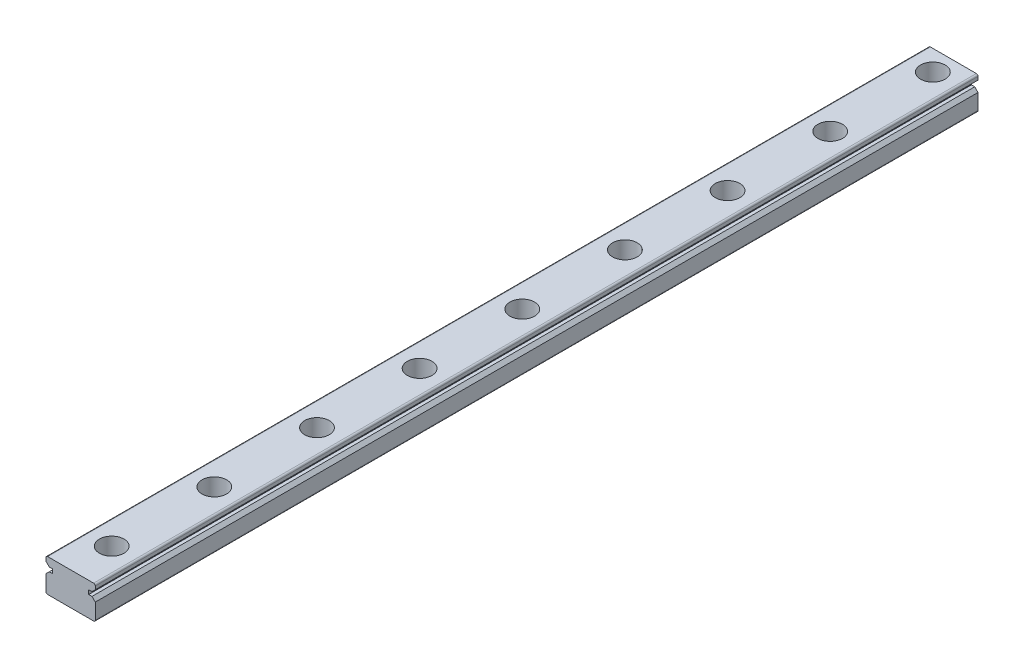
SolidWorks part; units mm, degrees
ref_plane "Front Plane" through (0, 0, 0) normal (0, 0, 1) x (1, 0, 0)
ref_plane "Top Plane" through (0, 0, 0) normal (0, 1, 0) x (1, 0, 0)
ref_plane "Right Plane" through (0, 0, 0) normal (1, 0, 0) x (0, 0, -1)
sketch "Sketch1" plane through (0, 0, 0) normal (0, 0, 1) x (1, 0, 0)
  line L0 (0, -1000) -> (0, 1.5) construction
  line L1 (-5.6, 4) -> (5.6, 4)
  line L2 (-6, 3.6) -> (-6, 2.8)
  line L3 (-5.6, -4) -> (5.6, -4)
  line L4 (6, 3.6) -> (6, 2.8)
  line L5 (-6, 4) -> (6, -4) construction
  line L6 (-6, -4) -> (6, 4) construction
  line L7 (6, 0.2) -> (6, -3.6)
  line L8 (-5.2, 2) -> (-4.4, 2)
  line L9 (-4.4, 2) -> (-4.4, 1)
  line L10 (-5.2, 1) -> (-4.4, 1)
  line L11 (4.4, 2) -> (4.4, 1)
  line L14 (-6, 0.2) -> (-6, -3.6)
  line L15 (4.4, 2) -> (5.2, 2)
  line L16 (4.4, 1) -> (5.2, 1)
  line L17 (0, 1.5) -> (0, 1001.8645) construction
  line L18 (-6, 2.8) -> (-5.2, 2)
  line L19 (-6, 0.2) -> (-5.2, 1)
  line L20 (5.2, 2) -> (6, 2.8)
  line L21 (5.2, 1) -> (6, 0.2)
  arc A0 (-6, -3.6) -> (-5.6, -4) centre (-5.6, -3.6) ccw
  arc A1 (5.6, -4) -> (6, -3.6) centre (5.6, -3.6) ccw
  arc A2 (5.6, 4) -> (6, 3.6) centre (5.6, 3.6) cw
  arc A3 (-5.6, 4) -> (-6, 3.6) centre (-5.6, 3.6) ccw
  point P0 (0, 0)
  point P13 (-6, 2)
  point P14 (6, 2)
  point P15 (6, 1)
  point P16 (-6, 1)
  dimension "D5" = 0.4
  dimension "D1" = 12
  dimension "D2" = 8
  dimension "D3" = 8.8
  dimension "D4" = 5
  dimension "D6" = 2
  dimension "D7" = 5
  dimension "D8" = 4.4
extrude "Boss-Extrude1" add sketch "Sketch1" along normal blind 215
sketch "Sketch2" plane through (0, 4, 0) normal (0, 1, 0) x (1, 0, 0)
  line L0 (5.6, -215) -> (-5.6, -215) construction
  circle A0 centre (0, -205) radius 3
  circle A1 centre (0, -180) radius 3
  circle A2 centre (0, -155) radius 3
  circle A3 centre (0, -130) radius 3
  circle A4 centre (0, -105) radius 3
  circle A5 centre (0, -80) radius 3
  circle A6 centre (0, -55) radius 3
  circle A7 centre (0, -30) radius 3
  circle A8 centre (0, -5) radius 3
  circle A9 centre (0, 20) radius 3
  circle A10 centre (0, 45) radius 3
  circle A11 centre (0, 70) radius 3
  circle A12 centre (0, 95) radius 3
  circle A13 centre (0, 120) radius 3
  circle A14 centre (0, 145) radius 3
  circle A15 centre (0, 170) radius 3
  circle A16 centre (0, 195) radius 3
  circle A17 centre (0, 220) radius 3
  point P39 (0, -215)
  dimension "D1" = 10
  dimension "D2" = 6
  dimension "D3" = 18
extrude "Cut-Extrude1" cut sketch "Sketch2" against normal blind 4.5
sketch "Sketch3" plane through (0, 4, 0) normal (0, 1, 0) x (1, 0, 0)
  line L0 (5.6, -215) -> (-5.6, -215) construction
  circle A2 centre (0, -205.0015) radius 1.75
  circle A3 centre (0, -180.0015) radius 1.75
  circle A4 centre (0, -155.0015) radius 1.75
  circle A5 centre (0, -130.0015) radius 1.75
  circle A6 centre (0, -105.0015) radius 1.75
  circle A7 centre (0, -80.0015) radius 1.75
  circle A8 centre (0, -55.0015) radius 1.75
  circle A9 centre (0, -30.0015) radius 1.75
  circle A10 centre (0, -5.0015) radius 1.75
  circle A11 centre (0, 19.9985) radius 1.75
  circle A12 centre (0, 44.9985) radius 1.75
  circle A13 centre (0, 69.9985) radius 1.75
  circle A14 centre (0, 94.9985) radius 1.75
  circle A15 centre (0, 119.9985) radius 1.75
  circle A16 centre (0, 144.9985) radius 1.75
  point P6 (0, -215)
  dimension "D1" = 3.5
  dimension "D2" = 9.9985
  dimension "D3" = 15
extrude "Cut-Extrude2" cut sketch "Sketch3" against normal through all
